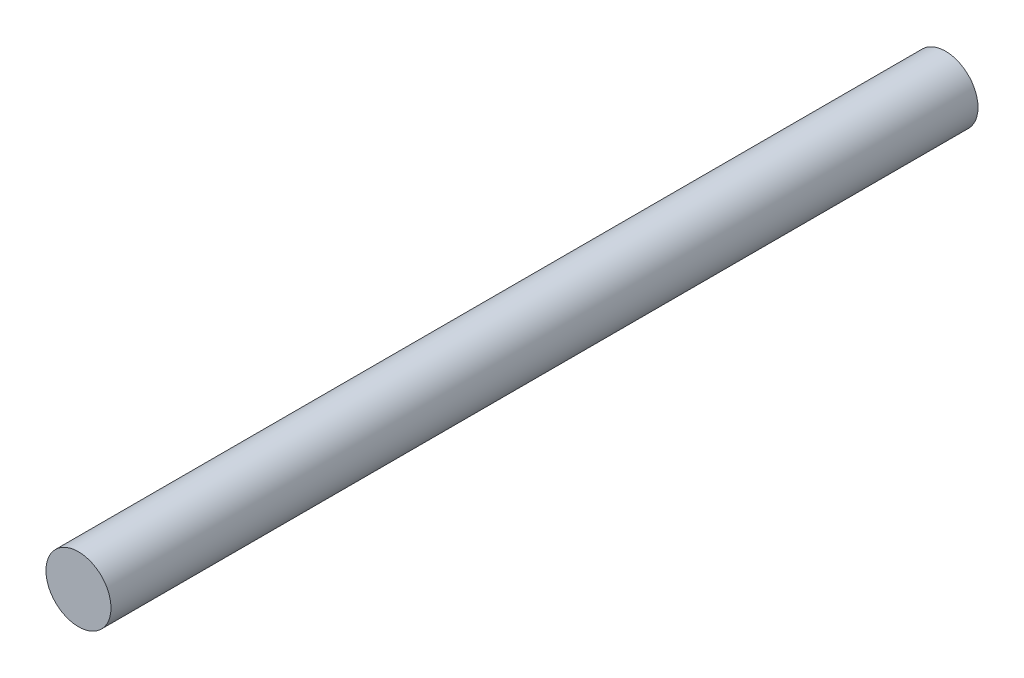
SolidWorks part; units mm, degrees
material "Laiton"
ref_plane "Plan de face" through (0, 0, 0) normal (0, 0, 1) x (1, 0, 0)
ref_plane "Plan de dessus" through (0, 0, 0) normal (0, 1, 0) x (1, 0, 0)
ref_plane "Plan de droite" through (0, 0, 0) normal (1, 0, 0) x (0, 0, -1)
sketch "Esquisse1" plane through (0, 0, 0) normal (0, 0, 1) x (1, 0, 0)
  circle A0 centre (0, 0) radius 1.5
  dimension "D1" = 3
extrude "Boss.-Extru.1" add sketch "Esquisse1" along normal blind 40
